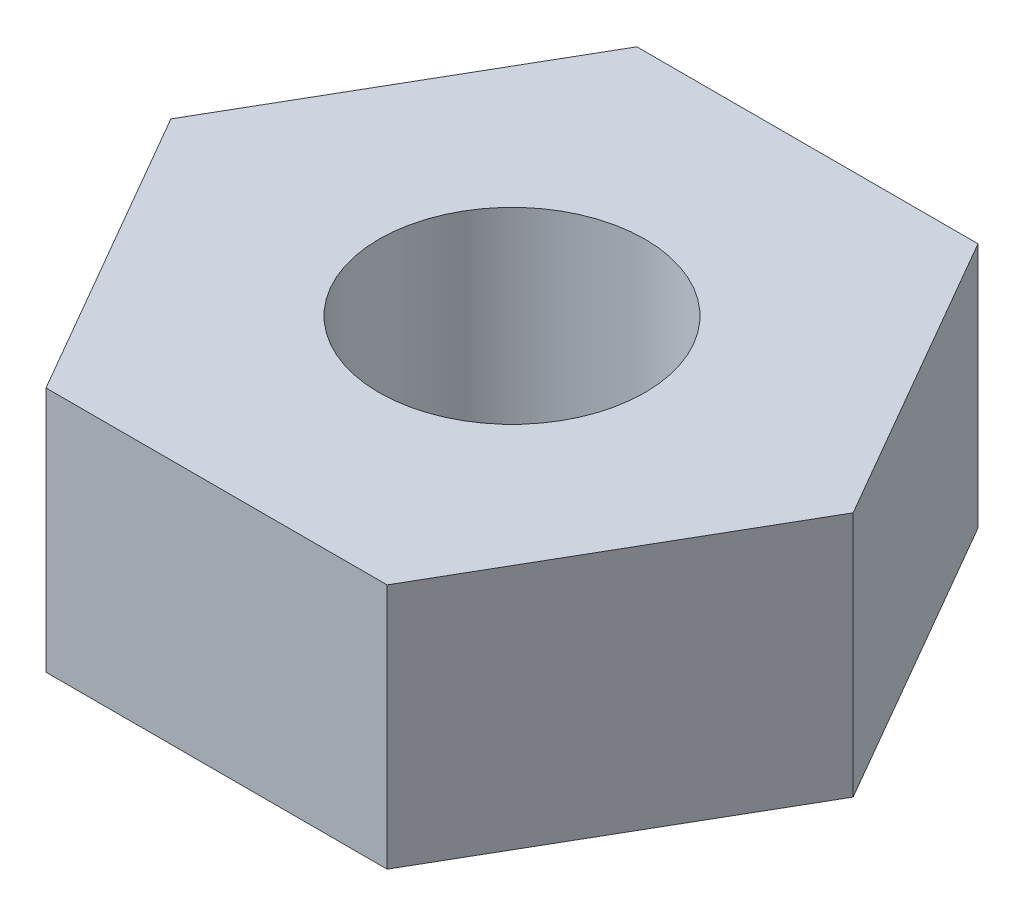
SolidWorks part; units mm, degrees
ref_plane "Front Plane" through (0, 0, 0) normal (0, 0, 1) x (1, 0, 0)
ref_plane "Top Plane" through (0, 0, 0) normal (0, 1, 0) x (1, 0, 0)
ref_plane "Right Plane" through (0, 0, 0) normal (1, 0, 0) x (0, 0, -1)
sketch "Sketch1" plane through (0, 0, 0) normal (0, 1, 0) x (1, 0, 0)
  line L1 (3.4641, 0) -> (1.7321, 3)
  line L2 (1.7321, 3) -> (-1.7321, 3)
  line L3 (-1.7321, 3) -> (-3.4641, 0)
  line L4 (-3.4641, 0) -> (-1.7321, -3)
  line L5 (-1.7321, -3) -> (1.7321, -3)
  line L6 (1.7321, -3) -> (3.4641, 0)
  circle A0 centre (0, 0) radius 3 construction
  circle A1 centre (0, 0) radius 1.35
  dimension "D2" = 2.7
  dimension "D1" = 6
extrude "Boss-Extrude1" add sketch "Sketch1" along normal blind 2.5
